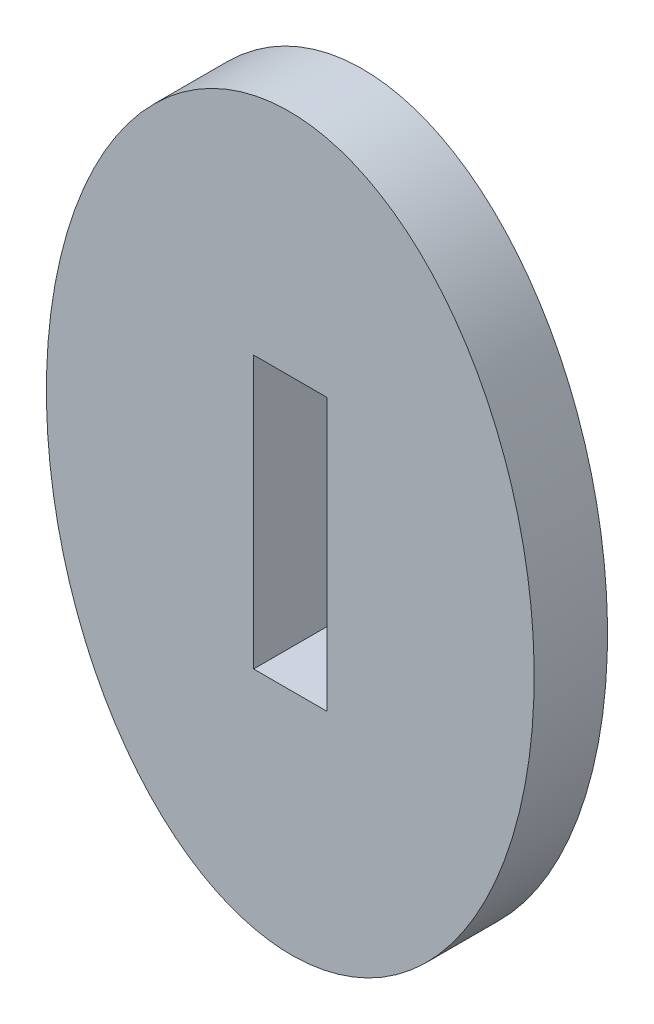
SolidWorks part; units mm, degrees
ref_plane "Front" through (0, 0, 0) normal (0, 0, 1) x (1, 0, 0)
ref_plane "Top" through (0, 0, 0) normal (0, 1, 0) x (1, 0, 0)
ref_plane "Right" through (0, 0, 0) normal (1, 0, 0) x (0, 0, -1)
sketch "Sketch1" plane through (0, 0, 0) normal (0, 0, 1) x (1, 0, 0)
  line L5 (-1.5, 5.56) -> (1.5, 5.56)
  line L6 (-1.5, 5.56) -> (-1.5, -5.56)
  line L7 (-1.5, -5.56) -> (1.5, -5.56)
  line L8 (1.5, 5.56) -> (1.5, -5.56)
  ellipse E0 centre (0, 0) end of major axis (0.0981, -14.9187) minor radius 9.9749
  point P9 (0, 0)
  dimension "D1" = 1.5
  dimension "D2" = 5.56
  dimension "D3" = 3
  dimension "D4" = 11.12
extrude "Base-Extrude" add sketch "Sketch1" along normal blind 3
